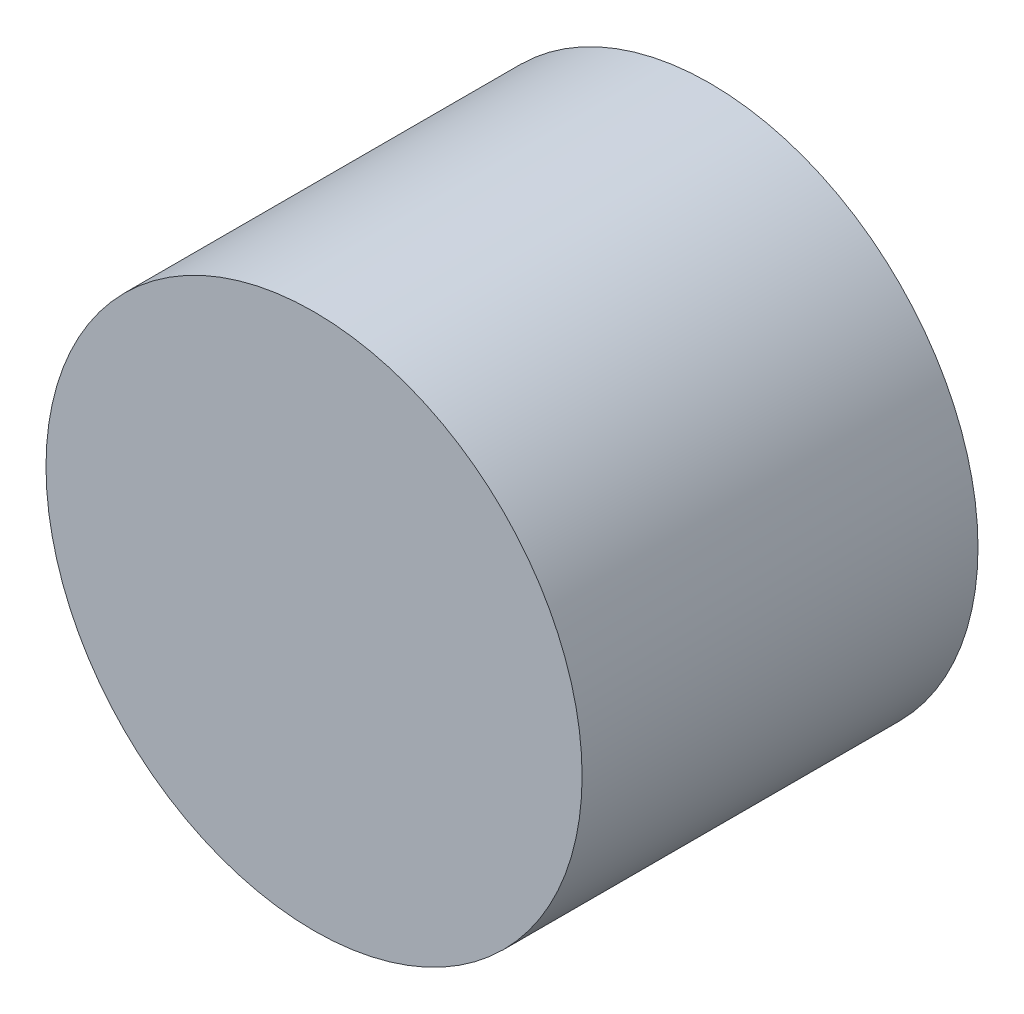
SolidWorks part; units mm, degrees
ref_plane "Front Plane" through (0, 0, 0) normal (0, 0, 1) x (1, 0, 0)
ref_plane "Top Plane" through (0, 0, 0) normal (0, 1, 0) x (1, 0, 0)
ref_plane "Right Plane" through (0, 0, 0) normal (1, 0, 0) x (0, 0, -1)
sketch "Sketch1" plane through (0, 0, 0) normal (0, 0, 1) x (1, 0, 0)
  circle A0 centre (0, 0) radius 103.1875
  dimension "D1" = 206.375
extrude "Boss-Extrude1" add sketch "Sketch1" along normal blind 152.4
sketch "Sketch2" plane through (0, 0, 0) normal (0, 0, -1) x (-1, 0, 0)
  circle A0 centre (0, 0) radius 101.6
  circle A1 centre (0, 0) radius 103.1875 construction
  dimension "D1" = 1.5875
extrude "Cut-Extrude1" cut sketch "Sketch2" against normal blind 149.225
sketch "Sketch3" plane through (0, 0, 0) normal (1, 0, 0) x (0, 0, -1)
  line L0 (-149.225, 0) -> (0, 0) construction
  line L1 (-149.225, -101.6) -> (-149.225, 101.6) construction
  line L2 (0, -103.1875) -> (0, 103.1875) construction
  line L3 (0, -101.6) -> (0, 101.6) construction
  circle A0 centre (-144.145, 0) radius 5.08
  dimension "D1" = 10.16
extrude "Cut-Extrude2" cut sketch "Sketch3" against normal through all
